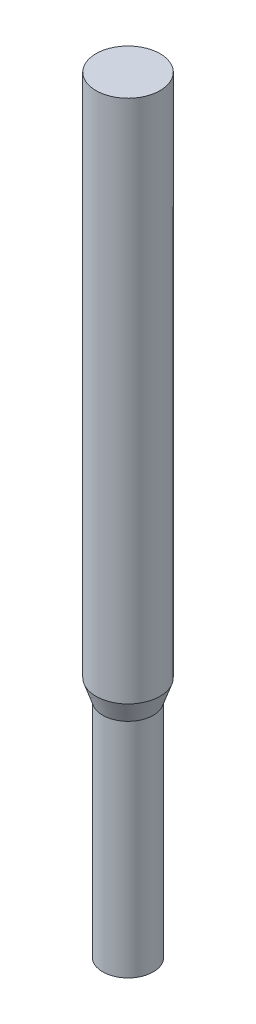
SolidWorks part; units mm, degrees
ref_plane "Front Plane" through (0, 0, 0) normal (0, 0, 1) x (1, 0, 0)
ref_plane "Top Plane" through (0, 0, 0) normal (0, 1, 0) x (1, 0, 0)
ref_plane "Right Plane" through (0, 0, 0) normal (1, 0, 0) x (0, 0, -1)
sketch "Sketch1" plane through (0, 0, 0) normal (0, 0, 1) x (1, 0, 0)
  line L0 (0, 0) -> (-1.5875, 0)
  line L1 (-1.5875, 0) -> (-1.5875, -26)
  line L2 (-1.5875, -26) -> (-1.25, -26.9839)
  line L3 (-1.25, -26.9839) -> (-1.25, -38)
  line L4 (-1.25, -38) -> (0, -38)
  line L5 (0, -38) -> (0, 0) construction
  line L6 (0, 0) -> (0, -38)
  point P3 (-1.25, -26.9839)
  dimension "D1" = 3.175
  dimension "D2" = 38
  dimension "D3" = 2.5
  dimension "D4" = 12
revolve "Revolve1" add sketch "Sketch1" angle 360 about L5
